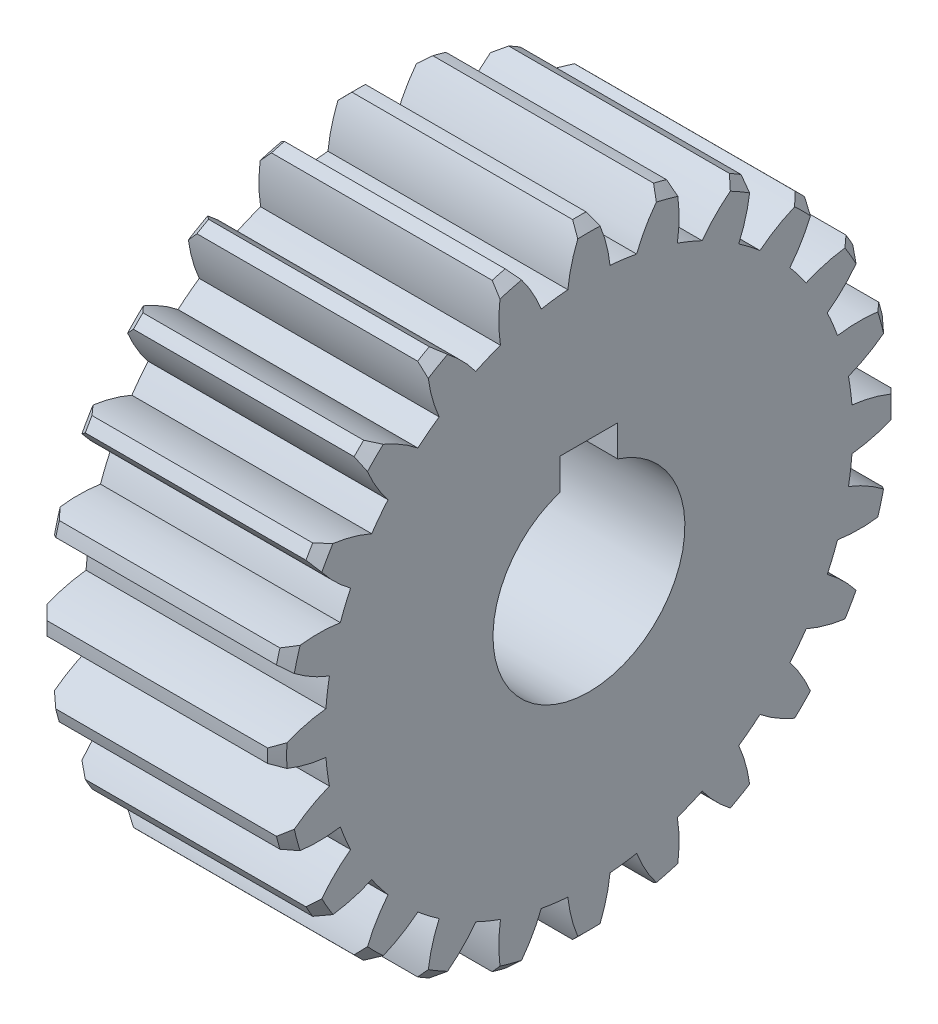
SolidWorks part; units mm, degrees
material "SUS304"
ref_plane "Front Plane" through (0, 0, 0) normal (0, 0, 1) x (1, 0, 0)
ref_plane "Top Plane" through (0, 0, 0) normal (0, 1, 0) x (1, 0, 0)
ref_plane "Right Plane" through (0, 0, 0) normal (1, 0, 0) x (0, 0, -1)
sketch "Sketch2" plane through (0, 0, 0) normal (0, 0, 1) x (1, 0, 0)
  line L0 (80.2193, 0) -> (0, 0) construction
  line L1 (0, 10) -> (25, 10)
  line L4 (25, 10) -> (25, 32.5)
  line L5 (25, 32.5) -> (0, 32.5)
  line L6 (0, 32.5) -> (0, 10)
  dimension "D1" = 20
  dimension "D2" = 65
  dimension "D3" = 25
revolve "Revolve1" add sketch "Sketch2" angle 360 about L0
chamfer "Chamfer1" distance 1 angle 45 2 edges at (0, 0, -32.5) (25, 0, -32.5)
sketch "Sketch3" plane through (0, 0, 0) normal (-1, 0, 0) x (0, 0, 1)
  line L0 (0, 0) -> (0, 32.5) construction
  line L1 (0, 7.036) -> (0, 12.8) construction
  line L2 (3, 8.2371) -> (3, 12.8)
  line L3 (-3, 8.2371) -> (-3, 12.8)
  line L4 (3, 8.2371) -> (-3, 8.2371)
  line L5 (3, 12.8) -> (-3, 12.8)
  line L6 (0, 8.2371) -> (0, 12.8) construction
  arc A0 (9.0858, 31.2041) -> (9.2197, 25.9084) centre (-5.6068, 28.183) cw
  arc A3 (15.64, 28.4893) -> (11.8007, 24.8394) centre (23.893, 15.9638) ccw
  arc A4 (0.7, 32.4925) -> (2.2, 27.4119) centre (-12.71, 25.7715) cw
  arc A5 (15.64, 28.4893) -> (9.0858, 31.2041) centre (0, 0) ccw
  arc A6 (11.8007, 24.8394) -> (9.2197, 25.9084) centre (0, 0) ccw
  arc A7 (7.7335, 31.5665) -> (4.9697, 27.0472) centre (18.9471, 21.6038) ccw
  arc A8 (16.8524, 27.7893) -> (15.6112, 22.6394) centre (1.8786, 28.6738) cw
  arc A9 (22.4807, 23.4706) -> (17.8275, 20.9387) centre (27.2106, 9.2359) ccw
  arc A10 (22.4807, 23.4706) -> (16.8524, 27.7893) centre (0, 0) ccw
  arc A11 (17.8275, 20.9387) -> (15.6112, 22.6394) centre (0, 0) ccw
  arc A12 (23.4706, 22.4807) -> (20.9387, 17.8275) centre (9.2359, 27.2106) cw
  arc A13 (27.7893, 16.8524) -> (22.6394, 15.6112) centre (28.6738, 1.8786) ccw
  arc A14 (27.7893, 16.8524) -> (23.4706, 22.4807) centre (0, 0) ccw
  arc A15 (22.6394, 15.6112) -> (20.9387, 17.8275) centre (0, 0) ccw
  arc A16 (28.4893, 15.64) -> (24.8394, 11.8007) centre (15.9638, 23.893) cw
  arc A17 (31.2041, 9.0858) -> (25.9084, 9.2197) centre (28.183, -5.6068) ccw
  arc A18 (31.2041, 9.0858) -> (28.4893, 15.64) centre (0, 0) ccw
  arc A19 (25.9084, 9.2197) -> (24.8394, 11.8007) centre (0, 0) ccw
  arc A20 (31.5665, 7.7335) -> (27.0472, 4.9697) centre (21.6038, 18.9471) cw
  arc A21 (32.4925, 0.7) -> (27.4119, 2.2) centre (25.7715, -12.71) ccw
  arc A22 (32.4925, 0.7) -> (31.5665, 7.7335) centre (0, 0) ccw
  arc A23 (27.4119, 2.2) -> (27.0472, 4.9697) centre (0, 0) ccw
  arc A24 (32.4925, -0.7) -> (27.4119, -2.2) centre (25.7715, 12.71) cw
  arc A25 (31.5665, -7.7335) -> (27.0472, -4.9697) centre (21.6038, -18.9471) ccw
  arc A26 (31.5665, -7.7335) -> (32.4925, -0.7) centre (0, 0) ccw
  arc A27 (27.0472, -4.9697) -> (27.4119, -2.2) centre (0, 0) ccw
  arc A28 (31.2041, -9.0858) -> (25.9084, -9.2197) centre (28.183, 5.6068) cw
  arc A29 (28.4893, -15.64) -> (24.8394, -11.8007) centre (15.9638, -23.893) ccw
  arc A30 (28.4893, -15.64) -> (31.2041, -9.0858) centre (0, 0) ccw
  arc A31 (24.8394, -11.8007) -> (25.9084, -9.2197) centre (0, 0) ccw
  arc A32 (27.7893, -16.8524) -> (22.6394, -15.6112) centre (28.6738, -1.8786) cw
  arc A33 (23.4706, -22.4807) -> (20.9387, -17.8275) centre (9.2359, -27.2106) ccw
  arc A34 (23.4706, -22.4807) -> (27.7893, -16.8524) centre (0, 0) ccw
  arc A35 (20.9387, -17.8275) -> (22.6394, -15.6112) centre (0, 0) ccw
  arc A36 (22.4807, -23.4706) -> (17.8275, -20.9387) centre (27.2106, -9.2359) cw
  arc A37 (16.8524, -27.7893) -> (15.6112, -22.6394) centre (1.8786, -28.6738) ccw
  arc A38 (16.8524, -27.7893) -> (22.4807, -23.4706) centre (0, 0) ccw
  arc A39 (15.6112, -22.6394) -> (17.8275, -20.9387) centre (0, 0) ccw
  arc A40 (15.64, -28.4893) -> (11.8007, -24.8394) centre (23.893, -15.9638) cw
  arc A41 (9.0858, -31.2041) -> (9.2197, -25.9084) centre (-5.6068, -28.183) ccw
  arc A42 (9.0858, -31.2041) -> (15.64, -28.4893) centre (0, 0) ccw
  arc A43 (9.2197, -25.9084) -> (11.8007, -24.8394) centre (0, 0) ccw
  arc A44 (7.7335, -31.5665) -> (4.9697, -27.0472) centre (18.9471, -21.6038) cw
  arc A45 (0.7, -32.4925) -> (2.2, -27.4119) centre (-12.71, -25.7715) ccw
  arc A46 (0.7, -32.4925) -> (7.7335, -31.5665) centre (0, 0) ccw
  arc A47 (2.2, -27.4119) -> (4.9697, -27.0472) centre (0, 0) ccw
  arc A48 (-0.7, -32.4925) -> (-2.2, -27.4119) centre (12.71, -25.7715) cw
  arc A49 (-7.7335, -31.5665) -> (-4.9697, -27.0472) centre (-18.9471, -21.6038) ccw
  arc A50 (-7.7335, -31.5665) -> (-0.7, -32.4925) centre (0, 0) ccw
  arc A51 (-4.9697, -27.0472) -> (-2.2, -27.4119) centre (0, 0) ccw
  arc A52 (7.7335, 31.5665) -> (0.7, 32.4925) centre (0, 0) ccw
  arc A53 (4.9697, 27.0472) -> (2.2, 27.4119) centre (0, 0) ccw
  arc A54 (-9.0858, -31.2041) -> (-9.2197, -25.9084) centre (5.6068, -28.183) cw
  arc A55 (-15.64, -28.4893) -> (-11.8007, -24.8394) centre (-23.893, -15.9638) ccw
  arc A56 (-15.64, -28.4893) -> (-9.0858, -31.2041) centre (0, 0) ccw
  arc A57 (-11.8007, -24.8394) -> (-9.2197, -25.9084) centre (0, 0) ccw
  arc A58 (-16.8524, -27.7893) -> (-15.6112, -22.6394) centre (-1.8786, -28.6738) cw
  arc A59 (-22.4807, -23.4706) -> (-17.8275, -20.9387) centre (-27.2106, -9.2359) ccw
  arc A60 (-22.4807, -23.4706) -> (-16.8524, -27.7893) centre (0, 0) ccw
  arc A61 (-17.8275, -20.9387) -> (-15.6112, -22.6394) centre (0, 0) ccw
  arc A62 (-23.4706, -22.4807) -> (-20.9387, -17.8275) centre (-9.2359, -27.2106) cw
  arc A63 (-27.7893, -16.8524) -> (-22.6394, -15.6112) centre (-28.6738, -1.8786) ccw
  arc A64 (-27.7893, -16.8524) -> (-23.4706, -22.4807) centre (0, 0) ccw
  arc A65 (-22.6394, -15.6112) -> (-20.9387, -17.8275) centre (0, 0) ccw
  arc A66 (-28.4893, -15.64) -> (-24.8394, -11.8007) centre (-15.9638, -23.893) cw
  arc A67 (-31.2041, -9.0858) -> (-25.9084, -9.2197) centre (-28.183, 5.6068) ccw
  arc A68 (-31.2041, -9.0858) -> (-28.4893, -15.64) centre (0, 0) ccw
  arc A69 (-25.9084, -9.2197) -> (-24.8394, -11.8007) centre (0, 0) ccw
  arc A70 (-31.5665, -7.7335) -> (-27.0472, -4.9697) centre (-21.6038, -18.9471) cw
  arc A71 (-32.4925, -0.7) -> (-27.4119, -2.2) centre (-25.7715, 12.71) ccw
  arc A72 (-32.4925, -0.7) -> (-31.5665, -7.7335) centre (0, 0) ccw
  arc A73 (-27.4119, -2.2) -> (-27.0472, -4.9697) centre (0, 0) ccw
  arc A74 (-32.4925, 0.7) -> (-27.4119, 2.2) centre (-25.7715, -12.71) cw
  arc A75 (-31.5665, 7.7335) -> (-27.0472, 4.9697) centre (-21.6038, 18.9471) ccw
  arc A76 (-31.5665, 7.7335) -> (-32.4925, 0.7) centre (0, 0) ccw
  arc A77 (-27.0472, 4.9697) -> (-27.4119, 2.2) centre (0, 0) ccw
  arc A78 (-31.2041, 9.0858) -> (-25.9084, 9.2197) centre (-28.183, -5.6068) cw
  arc A79 (-28.4893, 15.64) -> (-24.8394, 11.8007) centre (-15.9638, 23.893) ccw
  arc A80 (-28.4893, 15.64) -> (-31.2041, 9.0858) centre (0, 0) ccw
  arc A81 (-24.8394, 11.8007) -> (-25.9084, 9.2197) centre (0, 0) ccw
  arc A82 (-27.7893, 16.8524) -> (-22.6394, 15.6112) centre (-28.6738, 1.8786) cw
  arc A83 (-23.4706, 22.4807) -> (-20.9387, 17.8275) centre (-9.2359, 27.2106) ccw
  arc A84 (-23.4706, 22.4807) -> (-27.7893, 16.8524) centre (0, 0) ccw
  arc A85 (-20.9387, 17.8275) -> (-22.6394, 15.6112) centre (0, 0) ccw
  arc A86 (-22.4807, 23.4706) -> (-17.8275, 20.9387) centre (-27.2106, 9.2359) cw
  arc A87 (-16.8524, 27.7893) -> (-15.6112, 22.6394) centre (-1.8786, 28.6738) ccw
  arc A88 (-16.8524, 27.7893) -> (-22.4807, 23.4706) centre (0, 0) ccw
  arc A89 (-15.6112, 22.6394) -> (-17.8275, 20.9387) centre (0, 0) ccw
  arc A90 (-15.64, 28.4893) -> (-11.8007, 24.8394) centre (-23.893, 15.9638) cw
  arc A91 (-9.0858, 31.2041) -> (-9.2197, 25.9084) centre (5.6068, 28.183) ccw
  arc A92 (-9.0858, 31.2041) -> (-15.64, 28.4893) centre (0, 0) ccw
  arc A93 (-9.2197, 25.9084) -> (-11.8007, 24.8394) centre (0, 0) ccw
  arc A94 (-7.7335, 31.5665) -> (-4.9697, 27.0472) centre (-18.9471, 21.6038) cw
  arc A95 (-0.7, 32.4925) -> (-2.2, 27.4119) centre (12.71, 25.7715) ccw
  arc A97 (22.4807, 23.4706) -> (17.8275, 20.9387) centre (27.2106, 9.2359) ccw [skipped]
  arc A99 (27.7893, 16.8524) -> (22.6394, 15.6112) centre (28.6738, 1.8786) ccw [skipped]
  arc A101 (31.2041, 9.0858) -> (25.9084, 9.2197) centre (28.183, -5.6068) ccw [skipped]
  arc A103 (32.4925, 0.7) -> (27.4119, 2.2) centre (25.7715, -12.71) ccw [skipped]
  arc A105 (31.5665, -7.7335) -> (27.0472, -4.9697) centre (21.6038, -18.9471) ccw [skipped]
  arc A107 (28.4893, -15.64) -> (24.8394, -11.8007) centre (15.9638, -23.893) ccw [skipped]
  arc A109 (23.4706, -22.4807) -> (20.9387, -17.8275) centre (9.2359, -27.2106) ccw [skipped]
  arc A111 (16.8524, -27.7893) -> (15.6112, -22.6394) centre (1.8786, -28.6738) ccw [skipped]
  arc A113 (9.0858, -31.2041) -> (9.2197, -25.9084) centre (-5.6068, -28.183) ccw [skipped]
  arc A115 (0.7, -32.4925) -> (2.2, -27.4119) centre (-12.71, -25.7715) ccw [skipped]
  arc A117 (-7.7335, -31.5665) -> (-4.9697, -27.0472) centre (-18.9471, -21.6038) ccw [skipped]
  arc A119 (-15.64, -28.4893) -> (-11.8007, -24.8394) centre (-23.893, -15.9638) ccw [skipped]
  arc A121 (-22.4807, -23.4706) -> (-17.8275, -20.9387) centre (-27.2106, -9.2359) ccw [skipped]
  arc A123 (-27.7893, -16.8524) -> (-22.6394, -15.6112) centre (-28.6738, -1.8786) ccw [skipped]
  arc A125 (-31.2041, -9.0858) -> (-25.9084, -9.2197) centre (-28.183, 5.6068) ccw [skipped]
  arc A127 (-32.4925, -0.7) -> (-27.4119, -2.2) centre (-25.7715, 12.71) ccw [skipped]
  arc A129 (-31.5665, 7.7335) -> (-27.0472, 4.9697) centre (-21.6038, 18.9471) ccw [skipped]
  arc A131 (-28.4893, 15.64) -> (-24.8394, 11.8007) centre (-15.9638, 23.893) ccw [skipped]
  arc A133 (-23.4706, 22.4807) -> (-20.9387, 17.8275) centre (-9.2359, 27.2106) ccw [skipped]
  arc A136 (15.64, 28.4893) -> (11.8007, 24.8394) centre (23.893, 15.9638) ccw [skipped]
  arc A139 (-9.0858, 31.2041) -> (-9.2197, 25.9084) centre (5.6068, 28.183) ccw [skipped]
  arc A140 (-16.8524, 27.7893) -> (-15.6112, 22.6394) centre (-1.8786, 28.6738) ccw [skipped]
  arc A141 (-0.7, 32.4925) -> (-2.2, 27.4119) centre (12.71, 25.7715) ccw [skipped]
  arc A142 (-0.7, 32.4925) -> (-7.7335, 31.5665) centre (0, 0) ccw
  arc A143 (-2.2, 27.4119) -> (-4.9697, 27.0472) centre (0, 0) ccw
  circle A144 centre (0, 0) radius 32.5 construction
  circle A147 centre (0, 0) radius 10 construction
  dimension "D3" = 1.4
  dimension "D4" = 15
  dimension "D5" = 27.5
  dimension "D6" = 32.5
  dimension "D9" = 15
  dimension "D2" = 4.4
  dimension "D7" = 15.467
  dimension "D8" = 9.9393
  dimension "D12" = 2.8
  dimension "D10" = 3
  dimension "D11" = 3
extrude "Cut-Extrude1" cut sketch "Sketch3" against normal blind 56
equation "\"Mass Kg\"= \"SW-Mass\""
